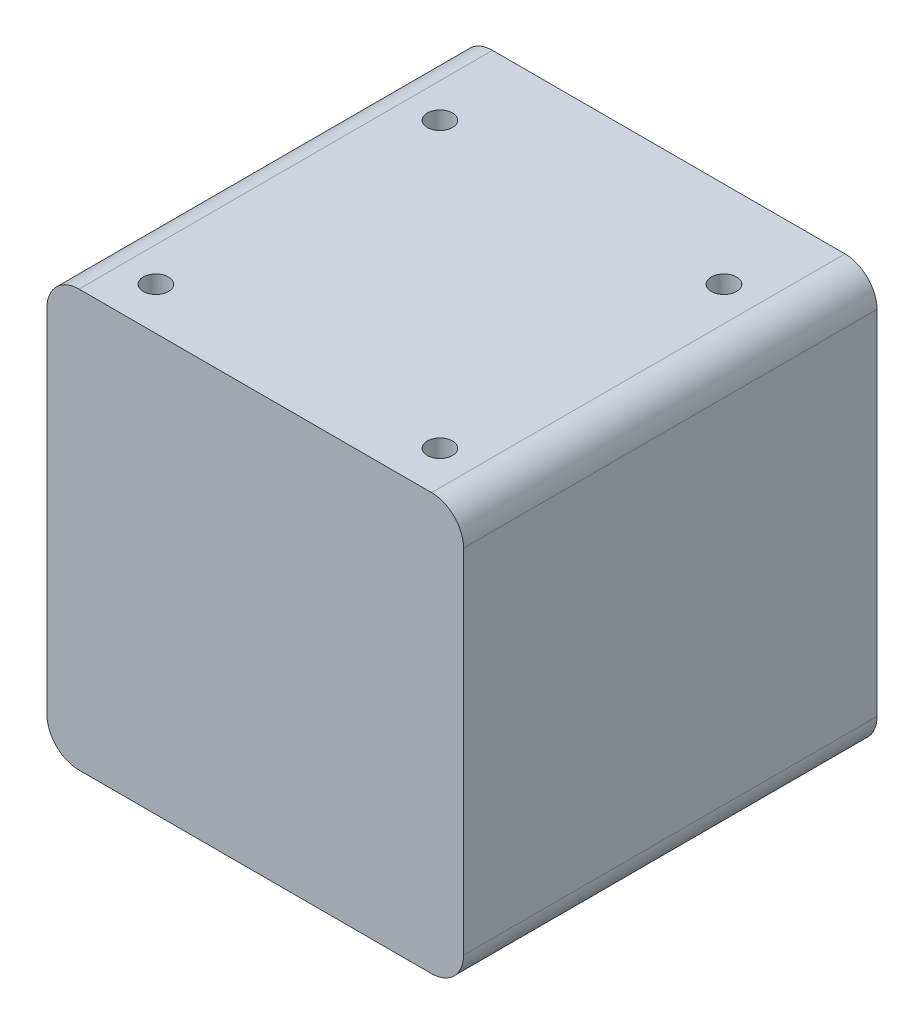
SolidWorks part; units mm, degrees
ref_plane "Front Plane" through (0, 0, 0) normal (0, 0, 1) x (1, 0, 0)
ref_plane "Top Plane" through (0, 0, 0) normal (0, 1, 0) x (1, 0, 0)
ref_plane "Right Plane" through (0, 0, 0) normal (1, 0, 0) x (0, 0, -1)
sketch "Sketch1" plane through (0, 0, 0) normal (0, 0, 1) x (1, 0, 0)
  line L1 (13.2, 13.2) -> (-13.2, 13.2)
  line L2 (13.2, 13.2) -> (13.2, -13.2)
  line L3 (13.2, -13.2) -> (-13.2, -13.2)
  line L4 (-13.2, 13.2) -> (-13.2, -13.2)
  line L5 (13.2, 13.2) -> (-13.2, -13.2) construction
  line L6 (13.2, -13.2) -> (-13.2, 13.2) construction
  point P0 (0, 0)
  dimension "D1" = 26.4
  dimension "D2" = 26.4
extrude "Boss-Extrude1" add sketch "Sketch1" along normal blind 26.2
fillet "Fillet1" radius 2.032 4 edges at (13.2, -13.2, 13.1) (-13.2, -13.2, 13.1) (-13.2, 13.2, 13.1) (13.2, 13.2, 13.1)
sketch "Sketch2" plane through (0, 13.2, 0) normal (0, 1, 0) x (1, 0, 0)
  line L0 (11.168, 0) -> (-11.168, 0) construction
  line L2 (0, 6.1973) -> (0, -24.5125) construction
  circle A0 centre (9, -5.5) radius 1
  circle A1 centre (9, -23.5) radius 1
  circle A2 centre (-9, -23.5) radius 1
  circle A3 centre (-9, -5.5) radius 1
  dimension "D1" = 2
  dimension "D3" = 18
  dimension "D4" = 18
  dimension "D2" = 5.5
sketch "Sketch4" plane through (0, -13.2, 0) normal (0, -1, 0) x (1, 0, 0)
  line L0 (0, -2.991) -> (0, -2.2561) construction
  line L1 (0, 25.5326) -> (0, -6.1715) construction
  line L3 (-11.168, 0) -> (11.168, 0) construction
  circle A0 centre (-9, 23.5) radius 1
  circle A1 centre (9, 23.5) radius 1
  circle A2 centre (9, 5.5) radius 1
  circle A3 centre (-9, 5.5) radius 1
  dimension "D1" = 2
  dimension "D2" = 18
  dimension "D4" = 18
  dimension "D3" = 5.5
sketch "Sketch5" plane through (0, 0, 0) normal (0, 0, -1) x (-1, 0, 0)
  circle A0 centre (0, 0) radius 12.6262
extrude "Cut-Extrude3" cut sketch "Sketch5" against normal blind 2.5
hole_wizard "M2x0.4 Tapped Hole1" positions "Sketch7" profile "Sketch6" tap size "M2x0.4" standard "ANSI Metric"
sketch "Sketch7" plane through (0, -13.2, 0) normal (0, -1, 0) x (-1, 0, 0)
  point P0 (9, -23.5)
  point P3 (9, -5.5)
  point P6 (-9, -5.5)
  point P9 (-9, -23.5)
sketch "Sketch6" plane through (-9, -13.2, 23.5) normal (1, 0, 0) x (0, 0, -1)
  line L0 (0, 0) -> (0, 5.334)
  line L1 (0, 5.334) -> (0.8, 5.334)
  line L2 (0.8, 5.334) -> (0.8, 0)
  line L5 (0.8, 0) -> (0, 0)
  line L10 (0, 5.334) -> (-0.8, 5.334) construction
  line L11 (0, -6.35) -> (0, 107.95) construction
  dimension "Tap Drill Dia." = 1.6
  dimension "Tap Drill Depth" = 5.334
  dimension "Drill Angle" = 180
cosmetic thread "Hole Thread1" parameters "D1"=4.064, "D2"=2
cosmetic thread "Hole Thread2" parameters "D1"=4.064, "D2"=2
cosmetic thread "Hole Thread3" parameters "D1"=4.064, "D2"=2
cosmetic thread "Hole Thread4" parameters "D1"=4.064, "D2"=2
hole_wizard "M2x0.4 Tapped Hole2" positions "Sketch9" profile "Sketch8" tap size "M2x0.4" standard "ANSI Metric"
sketch "Sketch9" plane through (0, 13.2, 0) normal (0, 1, 0) x (1, 0, 0)
  point P0 (9, -5.5)
  point P3 (9, -23.5)
  point P6 (-9, -23.5)
  point P9 (-9, -5.5)
sketch "Sketch8" plane through (9, 13.2, 5.5) normal (1, 0, 0) x (0, 0, 1)
  line L0 (0, 0) -> (0, 5.334)
  line L1 (0, 5.334) -> (0.8, 5.334)
  line L2 (0.8, 5.334) -> (0.8, 0)
  line L5 (0.8, 0) -> (0, 0)
  line L10 (0, 5.334) -> (-0.8, 5.334) construction
  line L11 (0, -6.35) -> (0, 107.95) construction
  dimension "Tap Drill Dia." = 1.6
  dimension "Tap Drill Depth" = 5.334
  dimension "Drill Angle" = 180
cosmetic thread "Hole Thread5" parameters "D1"=4.064, "D2"=2
cosmetic thread "Hole Thread6" parameters "D1"=4.064, "D2"=2
cosmetic thread "Hole Thread7" parameters "D1"=4.064, "D2"=2
cosmetic thread "Hole Thread8" parameters "D1"=4.064, "D2"=2
